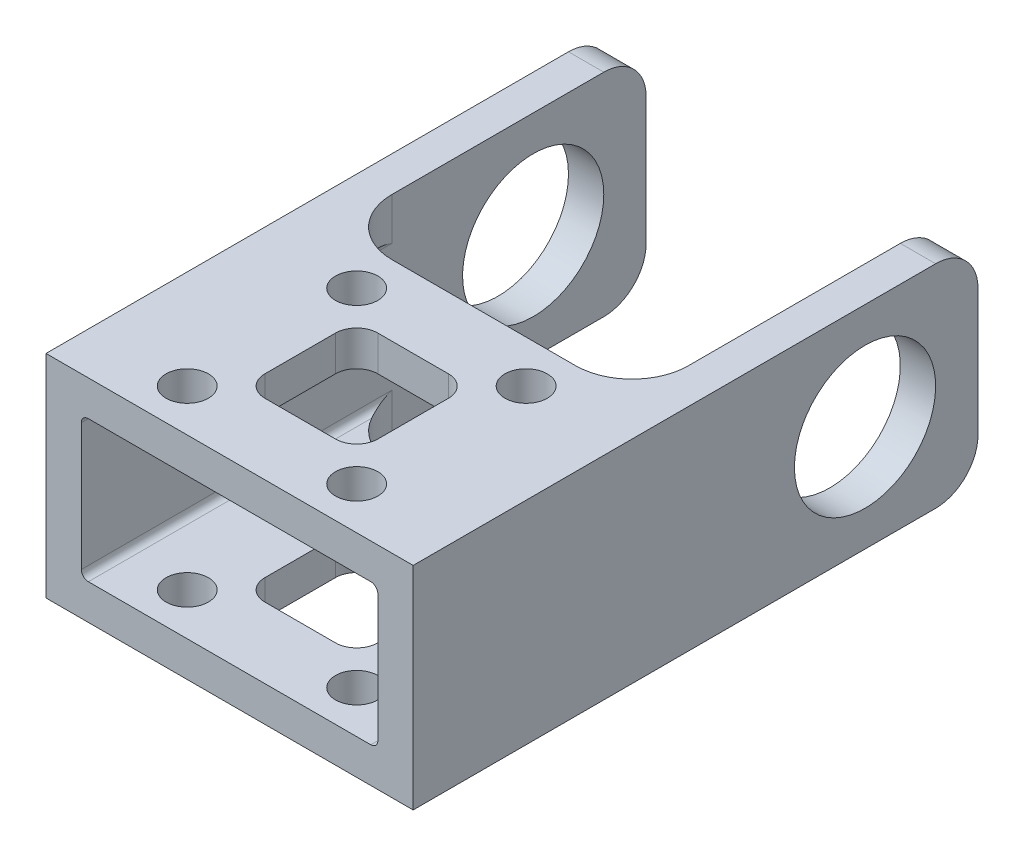
SolidWorks part; units mm, degrees
material "6061 合金"
ref_plane "前视基准面" through (0, 0, 0) normal (0, 0, 1) x (1, 0, 0)
ref_plane "上视基准面" through (0, 0, 0) normal (0, 1, 0) x (1, 0, 0)
ref_plane "右视基准面" through (0, 0, 0) normal (1, 0, 0) x (0, 0, -1)
sketch "草图1" plane through (0, 0, 0) normal (0, 0, 1) x (1, 0, 0)
  line L1 (0, 0) -> (23, 0)
  line L2 (0, 0) -> (0, 15)
  line L3 (0, 15) -> (23, 15)
  line L4 (23, 0) -> (23, 15)
  dimension "D1" = 15
  dimension "D2" = 23
extrude "凸台-拉伸1" add sketch "草图1" along normal blind 40
sketch "草图2" plane through (0, 0, 40) normal (0, 0, 1) x (1, 0, 0)
  line L0 (23, 2.5) -> (3, 2.5)
  line L1 (23, 0) -> (23, 15) construction
  line L2 (3, 2.5) -> (3, 12.5)
  line L3 (3, 12.5) -> (23, 12.5)
  line L4 (23, 12.5) -> (23, 2.5)
  line L5 (0, 0) -> (23, 0) construction
  line L6 (23, 15) -> (0, 15) construction
  line L7 (0, 15) -> (0, 0) construction
  dimension "D1" = 2.5
  dimension "D2" = 2.5
  dimension "D3" = 3
extrude "切除-拉伸2" cut sketch "草图2" against normal blind 68
sketch "草图5" plane through (0, 0, 0) normal (0, -1, 0) x (1, 0, 0)
  line L0 (0, 40) -> (0, 0) construction
  line L1 (23, 0) -> (3, 0)
  line L2 (23, 0) -> (23, 22)
  line L3 (23, 22) -> (3, 22)
  line L4 (3, 0) -> (3, 22)
  line L5 (0, 40) -> (23, 40) construction
  dimension "D1" = 3
  dimension "D2" = 18
extrude "切除-拉伸5" cut sketch "草图5" against normal blind 20
sketch "草图6" plane through (3, 0, 0) normal (1, 0, 0) x (0, 0, -1)
  line L0 (0, 0) -> (0, 15) construction
  line L1 (-22, 0) -> (0, 0) construction
  circle A0 centre (-8, 7.5) radius 5
  dimension "D1" = 10
  dimension "D2" = 8
  dimension "D3" = 7.5
extrude "切除-拉伸6" cut sketch "草图6" against normal blind 20
sketch "草图7" plane through (0, 0, 0) normal (0, -1, 0) x (1, 0, 0)
  line L0 (23, 22) -> (3, 22) construction
  line L1 (3, 40) -> (23, 40) construction
  line L2 (3, 40) -> (3, 22) construction
  line L3 (3, 22) -> (23, 22) construction
  line L4 (23, 40) -> (23, 22) construction
  line L5 (3, 40) -> (23, 22) construction
  line L6 (3, 22) -> (23, 40) construction
  line L8 (7, 25) -> (19, 25) construction
  line L9 (7, 25) -> (7, 37) construction
  line L10 (7, 37) -> (19, 37) construction
  line L11 (19, 25) -> (19, 37) construction
  line L12 (7, 25) -> (19, 37) construction
  line L13 (7, 37) -> (19, 25) construction
  line L14 (10.5, 27) -> (15.5, 27)
  line L15 (9, 28.5) -> (9, 33.5)
  line L16 (10.5, 35) -> (15.5, 35)
  line L17 (17, 28.5) -> (17, 33.5)
  line L18 (9, 27) -> (17, 35) construction
  line L19 (9, 35) -> (17, 27) construction
  circle A0 centre (7, 37) radius 1.5
  circle A1 centre (19, 37) radius 1.5
  circle A2 centre (7, 25) radius 1.5
  circle A3 centre (19, 25) radius 1.5
  arc A4 (15.5, 27) -> (17, 28.5) centre (15.5, 28.5) ccw
  arc A5 (10.5, 27) -> (9, 28.5) centre (10.5, 28.5) cw
  arc A6 (15.5, 35) -> (17, 33.5) centre (15.5, 33.5) cw
  arc A7 (9, 33.5) -> (10.5, 35) centre (10.5, 33.5) cw
  point P4 (13, 31)
  point P16 (13, 31)
  dimension "D4" = 3
  dimension "D5" = 8
  dimension "D7" = 1.5
  dimension "D1" = 20
  dimension "D2" = 12
  dimension "D3" = 12
  dimension "D6" = 8
extrude "切除-拉伸7" cut sketch "草图7" against normal blind 20
sketch "草图8" plane through (0, 0, 40) normal (0, 0, 1) x (1, 0, 0)
  line L6 (23, 15) -> (26, 15)
  line L7 (23, 15) -> (23, 0)
  line L8 (23, 0) -> (26, 0)
  line L9 (26, 15) -> (26, 0)
  dimension "D1" = 3
extrude "凸台-拉伸2" add sketch "草图8" against normal up to surface (40 mm away) up to face at (1.5, 7.5, 0)
sketch "草图9" plane through (0, 0, 40) normal (0, 0, 1) x (1, 0, 0)
  line L0 (3, 2.5) -> (23, 2.5) construction
  line L1 (2.5, 12.5) -> (23.5, 12.5)
  line L2 (2.5, 12.5) -> (2.5, 2.5)
  line L3 (2.5, 2.5) -> (23.5, 2.5)
  line L4 (23.5, 12.5) -> (23.5, 2.5)
  line L5 (23, 12.5) -> (3, 12.5) construction
  line L6 (23, 12.5) -> (23, 2.5) construction
  line L7 (3, 12.5) -> (3, 2.5) construction
  dimension "D1" = 0.5
  dimension "D2" = 0.5
extrude "切除-拉伸8" cut sketch "草图9" against normal blind 100
sketch "草图10" plane through (23, 0, 0) normal (-1, 0, 0) x (0, 0, 1)
  line L0 (0, 2.5) -> (22, 2.5) construction
  line L1 (22, 15) -> (0, 15)
  line L2 (22, 15) -> (22, 12.5)
  line L3 (22, 12.5) -> (0, 12.5)
  line L4 (0, 15) -> (0, 12.5)
  line L5 (22, 2.5) -> (0, 2.5)
  line L6 (22, 2.5) -> (22, 0)
  line L7 (22, 0) -> (0, 0)
  line L8 (0, 2.5) -> (0, 0)
  line L9 (22, 2.5) -> (22, 0) construction
extrude "切除-拉伸9" cut sketch "草图10" against normal blind 0.5 and the other way blind 20.5
fillet "圆角4" radius 0.5 4 edges at (2.5, 2.5, 31) (2.5, 12.5, 31) (23.5, 12.5, 31) (23.5, 2.5, 31)
sketch "草图11" plane through (23.5, 0, 0) normal (-1, 0, 0) x (0, 0, 1)
  circle A0 centre (8, 7.5) radius 5
  dimension "D1" = 10
extrude "切除-拉伸10" cut sketch "草图11" against normal blind 4.5
fillet "圆角5" radius 4 4 edges at (23.5, 13.5, 22) (23.5, 1.5, 22) (2.5, 13.5, 22) (2.5, 1.5, 22)
fillet "圆角6" radius 3 4 edges at (1.25, 15, 0) (1.25, 0, 0) (24.75, 15, 0) (24.75, 0, 0)
